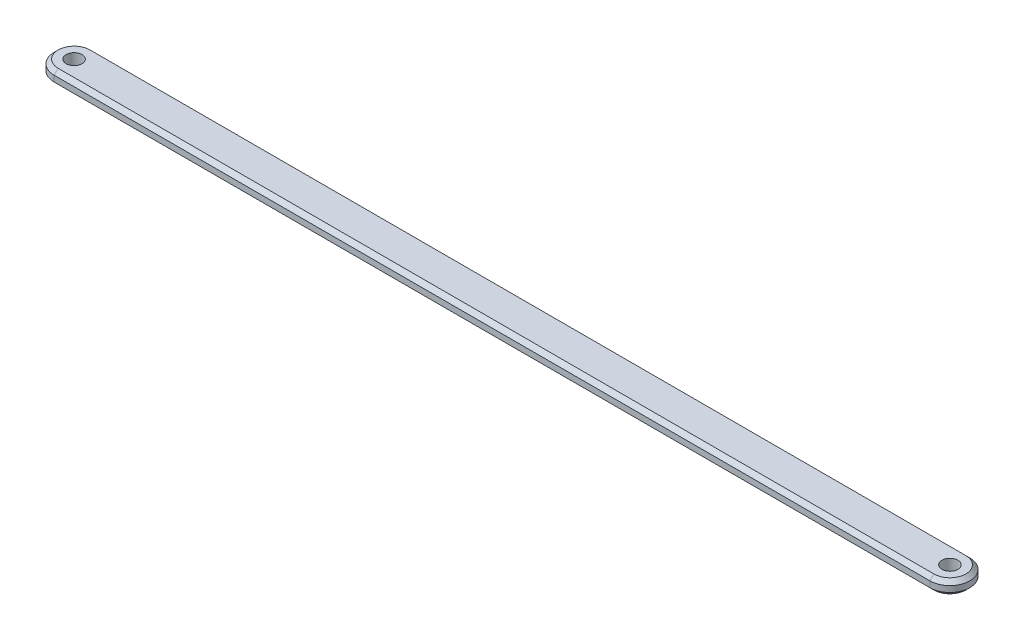
SolidWorks part; units mm, degrees
ref_plane "前视基准面" through (0, 0, 0) normal (0, 0, 1) x (1, 0, 0)
ref_plane "上视基准面" through (0, 0, 0) normal (0, 1, 0) x (1, 0, 0)
ref_plane "右视基准面" through (0, 0, 0) normal (1, 0, 0) x (0, 0, -1)
other "Configuration Table"
sketch "草图1" plane through (0, 0, 0) normal (0, 1, 0) x (1, 0, 0)
  line L0 (0, 5) -> (220, 5)
  line L1 (0, -5) -> (220, -5)
  line L2 (110, 5) -> (110, -5) construction
  arc A0 (0, 5) -> (0, -5) centre (0, 0) ccw
  circle A1 centre (0, 0) radius 2
  circle A2 centre (220, 0) radius 2
  arc A3 (220, 5) -> (220, -5) centre (220, 0) cw
  dimension "D1" = 10
  dimension "D2" = 4
  dimension "D3" = 110
extrude "凸台-拉伸1" add sketch "草图1" along normal blind 3.5
chamfer "倒角1" distance 1 angle 45 8 edges at (225, 3.5, 0) (110, 3.5, -5) (110, 3.5, 5) (-5, 3.5, 0) (225, 0, 0) (110, 0, -5) (110, 0, 5) (-5, 0, 0)
